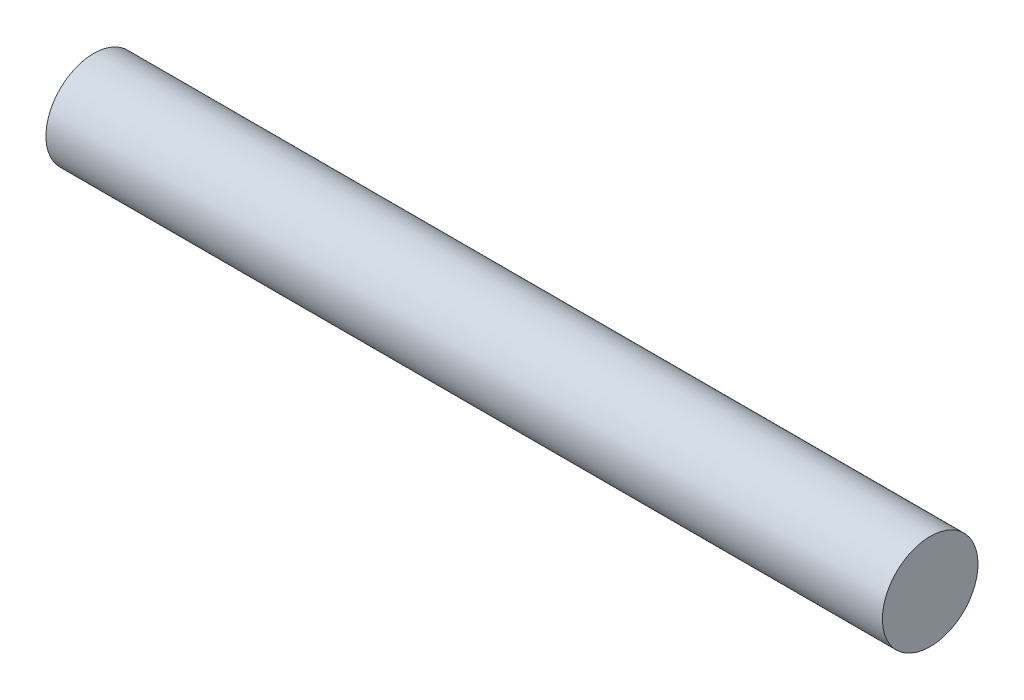
SolidWorks part; units mm, degrees
ref_plane "Front Plane" through (0, 0, 0) normal (0, 0, 1) x (1, 0, 0)
ref_plane "Top Plane" through (0, 0, 0) normal (0, 1, 0) x (1, 0, 0)
ref_plane "Right Plane" through (0, 0, 0) normal (1, 0, 0) x (0, 0, -1)
sketch "Sketch1" plane through (0, 0, 0) normal (1, 0, 0) x (0, 0, -1)
  circle A0 centre (0, 0) radius 8
  dimension "D1" = 16
extrude "Boss-Extrude1" add sketch "Sketch1" along normal blind 140
